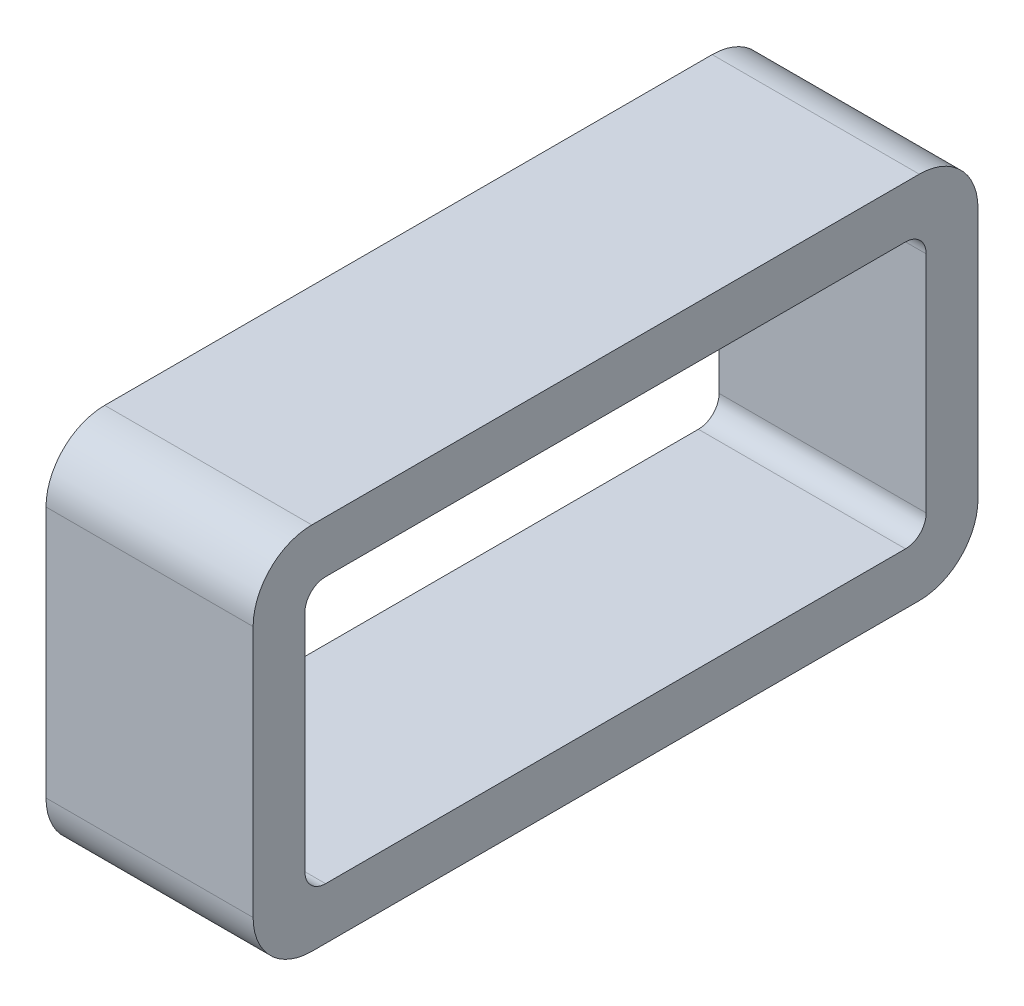
SolidWorks part; units mm, degrees
ref_plane "Front Plane" through (0, 0, 0) normal (0, 0, 1) x (1, 0, 0)
ref_plane "Top Plane" through (0, 0, 0) normal (0, 1, 0) x (1, 0, 0)
ref_plane "Right Plane" through (0, 0, 0) normal (1, 0, 0) x (0, 0, -1)
sketch "Sketch1" plane through (0, 0, 0) normal (1, 0, 0) x (0, 0, -1)
  line L1 (-9, 3.85) -> (9, 3.85)
  line L2 (-9, 3.85) -> (-9, -3.85)
  line L3 (-9, -3.85) -> (9, -3.85)
  line L4 (9, 3.85) -> (9, -3.85)
  line L5 (-9, 3.85) -> (9, -3.85) construction
  line L6 (-9, -3.85) -> (9, 3.85) construction
  line L7 (-10.5, 5.35) -> (10.5, 5.35)
  line L8 (-10.5, 5.35) -> (-10.5, -5.35)
  line L9 (-10.5, -5.35) -> (10.5, -5.35)
  line L10 (10.5, 5.35) -> (10.5, -5.35)
  line L11 (-10.5, 5.35) -> (10.5, -5.35) construction
  line L12 (-10.5, -5.35) -> (10.5, 5.35) construction
  point P0 (0, 0)
  point P6 (0, 0)
  dimension "D1" = 7.7
  dimension "D2" = 18
  dimension "D3" = 1.5
  dimension "D4" = 1.5
extrude "Boss-Extrude1" add sketch "Sketch1" along normal blind 6
fillet "Fillet1" radius 0.6 4 edges at (3, -3.85, -9) (3, 3.85, 9) (3, -3.85, 9) (3, 3.85, -9)
fillet "Fillet2" radius 1.7 4 edges at (3, -5.35, 10.5) (3, -5.35, -10.5) (3, 5.35, -10.5) (3, 5.35, 10.5)
